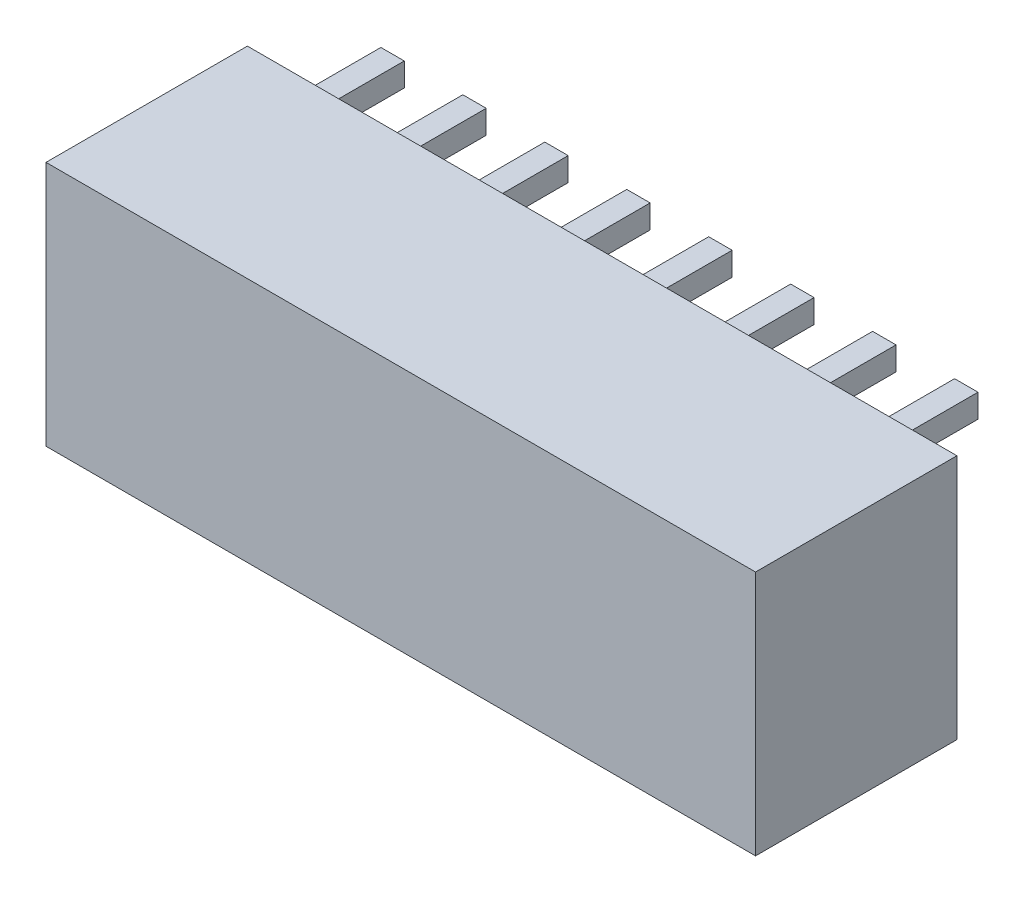
SolidWorks part; units mm, degrees
ref_plane "Спереди" through (0, 0, 0) normal (0, 0, 1) x (1, 0, 0)
ref_plane "Сверху" through (0, 0, 0) normal (0, 1, 0) x (1, 0, 0)
ref_plane "Справа" through (0, 0, 0) normal (1, 0, 0) x (0, 0, -1)
sketch "Эскиз1" plane through (0, 0, 0) normal (0, 0, 1) x (1, 0, 0)
  line L1 (-15.15, -5.25) -> (15.15, -5.25)
  line L2 (-15.15, -5.25) -> (-15.15, 5.25)
  line L3 (-15.15, 5.25) -> (15.15, 5.25)
  line L4 (15.15, -5.25) -> (15.15, 5.25)
  line L5 (-15.15, -5.25) -> (15.15, 5.25) construction
  line L6 (-15.15, 5.25) -> (15.15, -5.25) construction
  point P0 (0, 0)
  dimension "D1" = 30.3
  dimension "D2" = 10.5
extrude "Бобышка-Вытянуть1" add sketch "Эскиз1" along normal blind 8.6
sketch "Эскиз2" plane through (0, -5.25, 0) normal (0, -1, 0) x (1, 0, 0)
  line L0 (-14.15, 6.6) -> (14.15, 6.6)
  line L1 (14.15, 6.6) -> (14.15, 0.2)
  line L2 (14.15, 0.2) -> (11.95, 0.2)
  line L3 (11.95, 0.2) -> (11.95, 1.8)
  line L4 (11.95, 1.8) -> (-10.35, 1.8)
  line L5 (-10.35, 1.8) -> (-10.35, 0.2)
  line L6 (-10.35, 0.2) -> (-12.55, 0.2)
  line L7 (-14.15, 6.6) -> (-14.15, 1.8)
  line L8 (-14.15, 1.8) -> (-12.55, 1.8)
  line L9 (-12.55, 1.8) -> (-12.55, 0.2)
  line L10 (15.15, 8.6) -> (15.15, 0) construction
  line L11 (-15.15, 8.6) -> (-15.15, 0) construction
  line L12 (-15.15, 8.6) -> (15.15, 8.6) construction
  dimension "D1" = 4.8
  dimension "D2" = 6.4
  dimension "D3" = 2.2
  dimension "D4" = 2.2
  dimension "D5" = 3.2
  dimension "D6" = 4.8
  dimension "D7" = 1
  dimension "D8" = 2
extrude "Вырез-Вытянуть1" cut sketch "Эскиз2" against normal blind 7
sketch "Эскиз3" plane through (0, 0, 0) normal (0, 0, -1) x (-1, 0, 0)
  line L0 (15.15, -5.25) -> (-15.15, -5.25) construction
  line L1 (12.75, 4.75) -> (11.75, 4.75)
  line L2 (12.75, 4.75) -> (12.75, 3.75)
  line L3 (12.75, 3.75) -> (11.75, 3.75)
  line L4 (11.75, 4.75) -> (11.75, 3.75)
  line L5 (12.75, 4.75) -> (11.75, 3.75) construction
  line L6 (12.75, 3.75) -> (11.75, 4.75) construction
  line L7 (15.15, 5.25) -> (15.15, -5.25) construction
  point P0 (12.25, 4.25)
  dimension "D1" = 1
  dimension "D2" = 9.5
  dimension "D3" = 2.9
extrude "Бобышка-Вытянуть2" add sketch "Эскиз3" along normal blind 3.6 and the other way blind 5
chamfer "Фаска1" distance 0.3 distance2 0.3 4 edges at (-11.75, 4.25, -3.6) (-12.25, 3.75, -3.6) (-12.75, 4.25, -3.6) (-12.25, 4.75, -3.6)
pattern_linear "Линейный массив1" count 8 spacing 3.5 along (1, 0, 0) of "Бобышка-Вытянуть2", "Фаска1"
equation "\"N\"= 8"
equation "\"D1@Эскиз1\"= ( \"N\" - 1 ) * 3.5 + 5.8"
equation "\"D1@Линейный массив1\"=\"N\""
